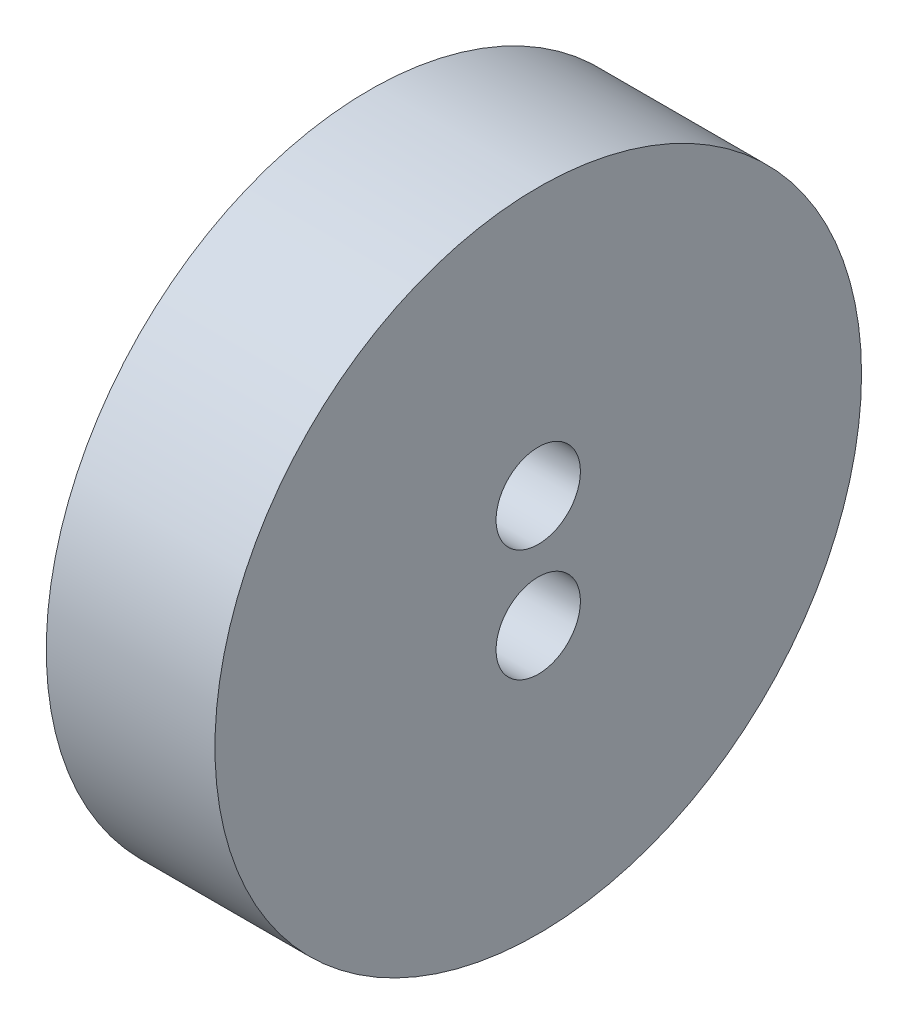
SolidWorks part; units mm, degrees
ref_plane "Front" through (0, 0, 0) normal (0, 0, 1) x (1, 0, 0)
ref_plane "Top" through (0, 0, 0) normal (0, 1, 0) x (1, 0, 0)
ref_plane "Right" through (0, 0, 0) normal (1, 0, 0) x (0, 0, -1)
sketch "Sketch1" plane through (0, 0, 0) normal (1, 0, 0) x (0, 0, -1)
  line L0 (0, -11.5) -> (0, 11.5) construction
  circle A0 centre (0, 0) radius 11.5
  circle A1 centre (0, 2) radius 1.5
  circle A2 centre (0, -2) radius 1.5
  point P6 (0, 0)
  dimension "D1" = 23
  dimension "D2" = 2
  dimension "D3" = 3
  dimension "D4" = 2
extrude "Boss-Extrude1" add sketch "Sketch1" along normal blind 6
